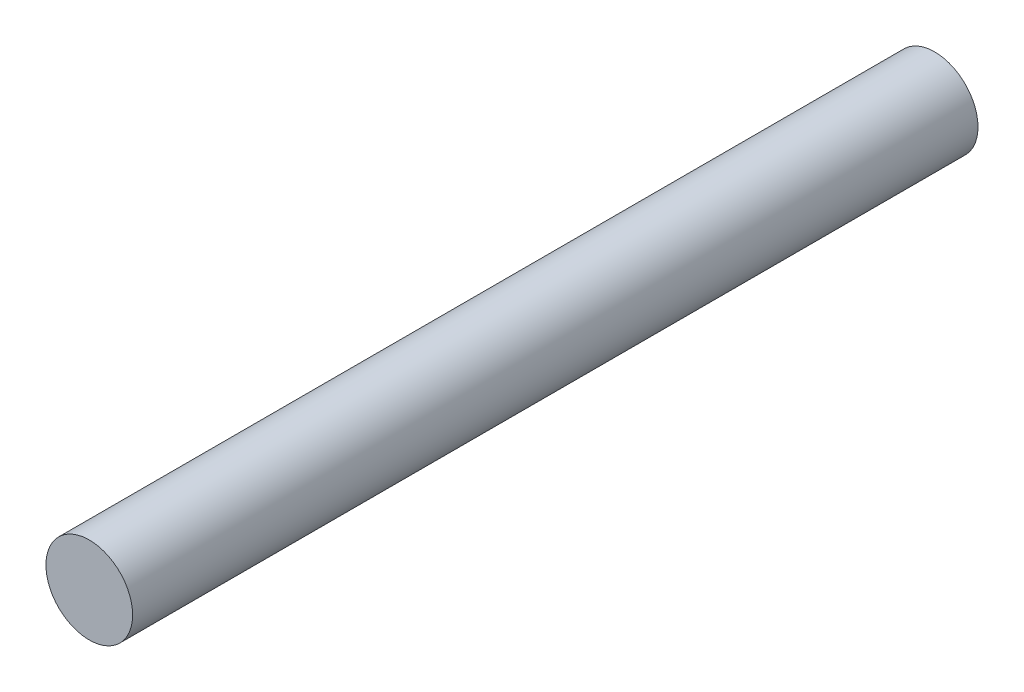
SolidWorks part; units mm, degrees
material "ABS PC"
ref_plane "Front Plane" through (0, 0, 0) normal (0, 0, 1) x (1, 0, 0)
ref_plane "Top Plane" through (0, 0, 0) normal (0, 1, 0) x (1, 0, 0)
ref_plane "Right Plane" through (0, 0, 0) normal (1, 0, 0) x (0, 0, -1)
sketch "Sketch1" plane through (0, 0, 0) normal (0, 0, 1) x (1, 0, 0)
  circle A0 centre (0, 0) radius 4
  dimension "D1" = 8
extrude "Boss-Extrude1" add sketch "Sketch1" along normal blind 78
